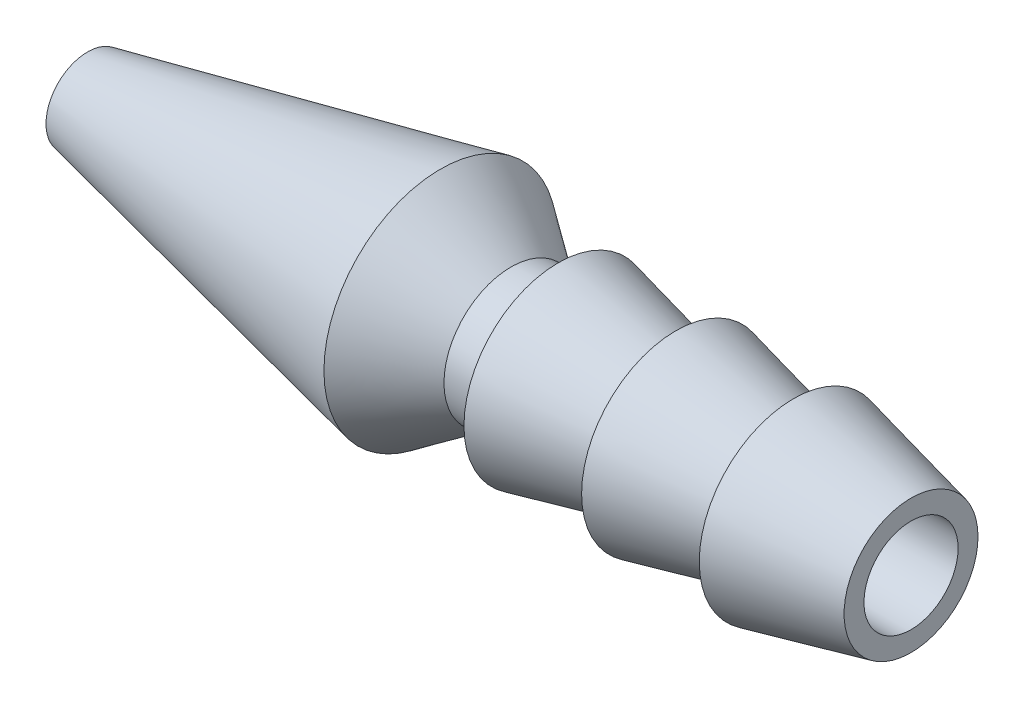
SolidWorks part; units mm, degrees
ref_plane "Front Plane" through (0, 0, 0) normal (0, 0, 1) x (1, 0, 0)
ref_plane "Top Plane" through (0, 0, 0) normal (0, 1, 0) x (1, 0, 0)
ref_plane "Right Plane" through (0, 0, 0) normal (1, 0, 0) x (0, 0, -1)
sketch "Sketch1" plane through (0, 0, 0) normal (1, 0, 0) x (0, 0, -1)
  circle A0 centre (0, 0) radius 4
extrude "Boss-Extrude1" add sketch "Sketch1" along normal blind 5 draft 13
sketch "Sketch2" plane through (5, 0, 0) normal (1, 0, 0) x (0, 0, -1)
  circle A0 centre (0, 0) radius 4
extrude "Boss-Extrude2" add sketch "Sketch2" along normal blind 5 draft 13
sketch "Sketch3" plane through (10, 0, 0) normal (1, 0, 0) x (0, 0, -1)
  circle A0 centre (0, 0) radius 4
extrude "Boss-Extrude3" add sketch "Sketch3" along normal blind 5 draft 13
sketch "Sketch4" plane through (0, 0, 0) normal (-1, 0, 0) x (0, 0, 1)
  circle A0 centre (0, 0) radius 2.85
extrude "Boss-Extrude4" add sketch "Sketch4" along normal blind 2
sketch "Sketch5" plane through (-2, 0, 0) normal (-1, 0, 0) x (0, 0, 1)
  circle A0 centre (0, 0) radius 2.85
extrude "Boss-Extrude5" add sketch "Sketch5" along normal blind 3 draft 35 draft outward yes
sketch "Sketch6" plane through (-5, 0, 0) normal (-1, 0, 0) x (0, 0, 1)
  circle A0 centre (0, 0) radius 4.9506
extrude "Boss-Extrude6" add sketch "Sketch6" along normal blind 15 draft 12
sketch "Sketch9" plane through (15, 0, 0) normal (1, 0, 0) x (0, 0, -1)
  circle A0 centre (0, 0) radius 2
extrude "Cut-Extrude1" cut sketch "Sketch9" against normal blind 20
sketch "Sketch14" plane through (-5, 0, 0) normal (1, 0, 0) x (0, 0, -1)
  circle A0 centre (0, 0) radius 2
extrude "Cut-Extrude11" cut sketch "Sketch14" against normal blind 10 draft 11.2
sketch "Sketch15" plane through (-20, 0, 0) normal (-1, 0, 0) x (0, 0, 1)
  line L0 (0, 1.3089) -> (0, 0.9)
  line L1 (-1.3089, 0) -> (-0.9, 0)
  line L2 (0, -1.3089) -> (0, -0.9)
  line L3 (1.3089, 0) -> (0.9, 0)
  line L4 (-1.3057, 0.0919) -> (1.3057, 0.0919)
  line L5 (1.3057, -0.0919) -> (-1.3057, -0.0919)
  line L6 (-0.105, 1.3047) -> (-0.105, -1.3047)
  line L7 (0.1129, -1.2974) -> (0.1129, 1.3064)
  circle A0 centre (0, 0) radius 0.9
  circle A1 centre (0, 0) radius 1.3089
extrude "Cut-Extrude13" cut sketch "Sketch15" against normal blind 10
